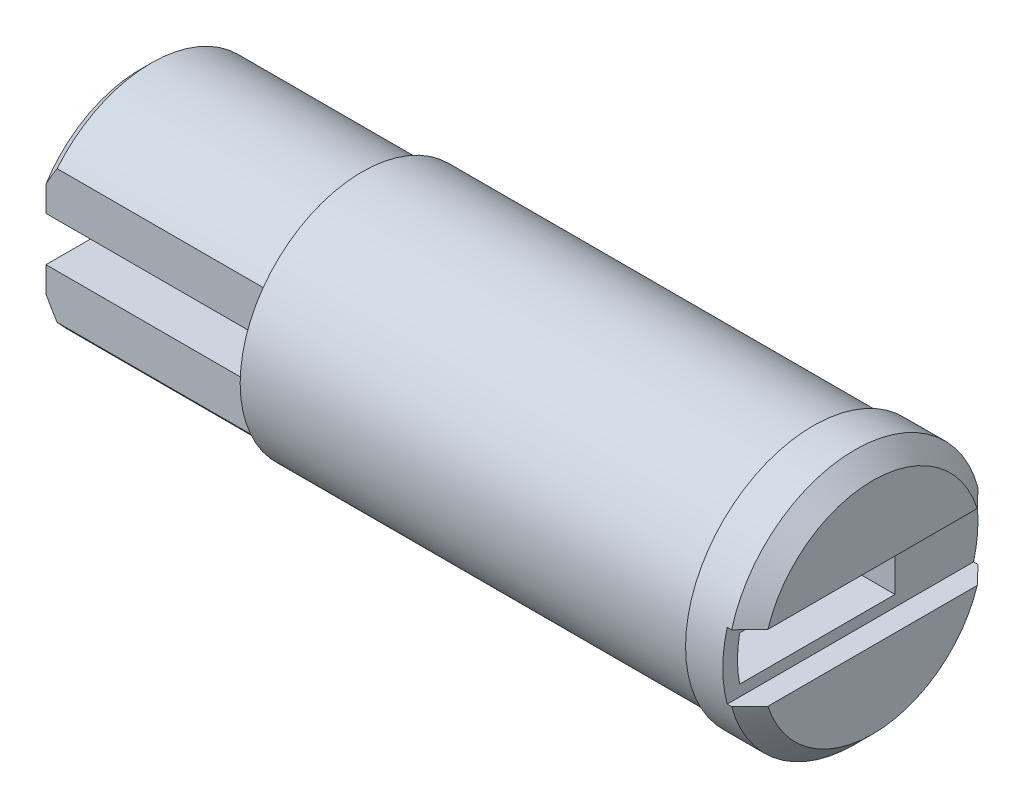
SolidWorks part; units mm, degrees
ref_plane "Front Plane" through (0, 0, 0) normal (0, 0, 1) x (1, 0, 0)
ref_plane "Top Plane" through (0, 0, 0) normal (0, 1, 0) x (1, 0, 0)
ref_plane "Right Plane" through (0, 0, 0) normal (1, 0, 0) x (0, 0, -1)
sketch "Sketch1" plane through (0, 0, 0) normal (0, 0, 1) x (1, 0, 0)
  line L0 (0, 0) -> (31, 0) construction
  line L1 (31, 0) -> (31, 5.75)
  line L2 (31, 5.75) -> (28.3219, 5.75)
  line L3 (28.3219, 5.75) -> (28.3219, 5.5)
  line L4 (28.3219, 5.5) -> (0, 5.5)
  line L5 (0, 5.5) -> (0, 0)
  line L6 (0, 0) -> (31, 0)
  dimension "D1" = 31
  dimension "D2" = 5.5
  dimension "D3" = 5.75
revolve "Revolve1" add sketch "Sketch1" angle 360 about L0
chamfer "Chamfer1" distance 0.8 angle 45 1 edges at (31, 0, 5.75)
chamfer "Chamfer2" distance 1 angle 45 1 edges at (0, 0, 5.5)
sketch "Sketch3" plane through (31, 0, 0) normal (1, 0, 0) x (0, 0, -1)
  line L0 (0, 0) -> (5.75, 0) construction
  line L2 (6.4757, 1.5) -> (-7.8139, 1.5)
  line L3 (6.4757, 1.5) -> (6.4757, -1.5)
  line L4 (6.4757, -1.5) -> (-7.8139, -1.5)
  line L5 (-7.8139, 1.5) -> (-7.8139, -1.5)
  circle A0 centre (0, 0) radius 5.75 construction
  dimension "D1" = 3
extrude "Cut-Extrude1" cut sketch "Sketch3" against normal blind 1
sketch "Sketch5" plane through (0, 0, 0) normal (-1, 0, 0) x (0, 0, 1)
  circle A0 centre (0, 0) radius 8.9874
extrude "Cut-Extrude3" cut sketch "Sketch5" against normal blind 8
sketch "Sketch6" plane through (8, 0, 0) normal (-1, 0, 0) x (0, 0, 1)
  line L0 (-4.25, -3) -> (4.25, 3) construction
  line L1 (-4.25, 3) -> (-4.25, -3)
  line L2 (4.25, 3) -> (4.25, -3)
  line L3 (-4.25, 3) -> (4.25, -3) construction
  arc A0 (-4.25, 3) -> (4.25, 3) centre (0, -0.5156) cw
  arc A1 (-4.25, -3) -> (4.25, -3) centre (0, 0.5156) ccw
  point P10 (0, -5)
  dimension "D2" = 8.5
extrude "Boss-Extrude1" add sketch "Sketch6" along normal blind 10
chamfer "Chamfer3" distance 0.5 angle 45 4 edges at (-2, 0, -4.25) (-2, -5, 0) (-2, 0, 4.25) (-2, 5, 0)
sketch "Sketch7" plane through (30, 0, 0) normal (1, 0, 0) x (0, 0, -1)
  line L0 (0, 0) -> (-7.0294, 0) construction
  line L2 (2.0098, 1) -> (-4.9902, 1)
  line L3 (2.0098, 1) -> (2.0098, -1)
  line L4 (2.0098, -1) -> (-4.9902, -1)
  arc A0 (-4.9902, 1) -> (-4.9902, -1) centre (0, 0) ccw
  arc A1 (-5.5509, 1.5) -> (-5.5509, -1.5) centre (0, 0) ccw construction
  dimension "D2" = 5.0894
  dimension "D1" = 7
  dimension "D3" = 2
extrude "Cut-Extrude4" cut sketch "Sketch7" against normal blind 35
